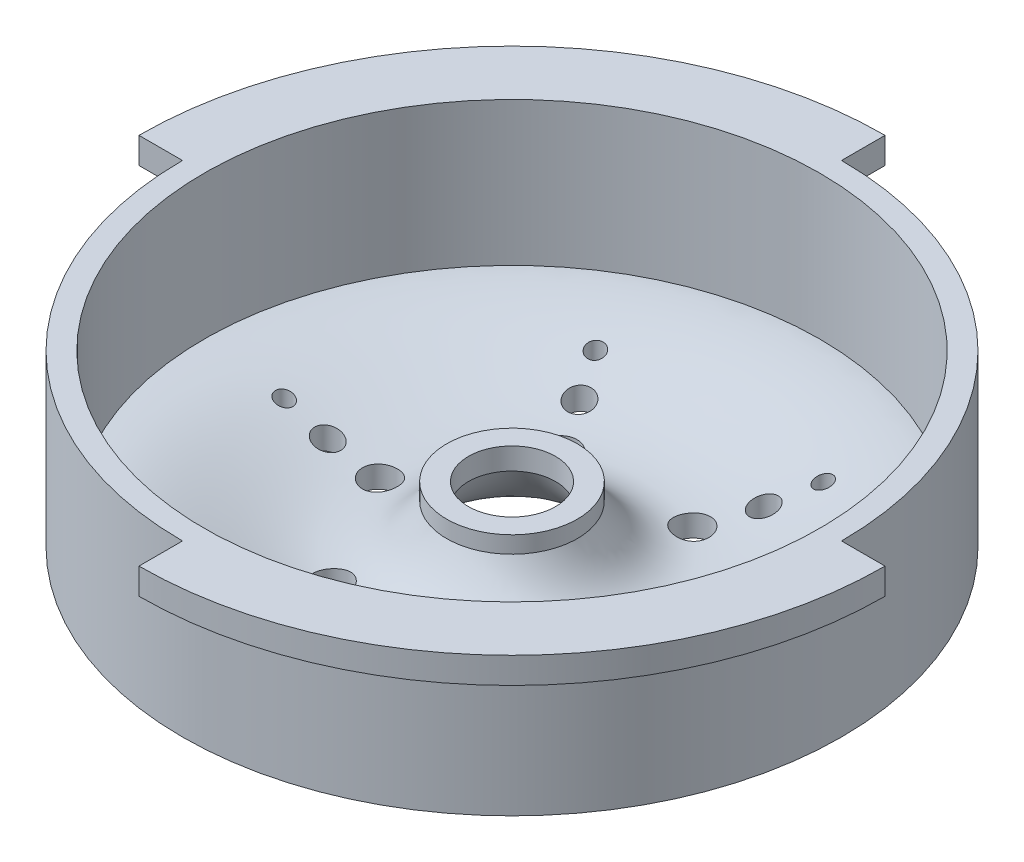
SolidWorks part; units mm, degrees
ref_plane "Front Plane" through (0, 0, 0) normal (0, 0, 1) x (1, 0, 0)
ref_plane "Top Plane" through (0, 0, 0) normal (0, 1, 0) x (1, 0, 0)
ref_plane "Right Plane" through (0, 0, 0) normal (1, 0, 0) x (0, 0, -1)
sketch "Sketch1" plane through (0, 0, 0) normal (0, 0, 1) x (1, 0, 0)
  line L0 (0, 0) -> (0, 16.7848) construction
  line L1 (-12.7, 9.2472) -> (-12.7, 15.5972)
  line L4 (-96.0794, 48.6172) -> (-89.7294, 48.6172)
  line L5 (-19.05, 10.682) -> (-19.05, 15.5972)
  line L8 (-89.7294, 42.2672) -> (-89.7294, 42.2672)
  line L9 (-19.05, 15.5972) -> (-12.7, 15.5972)
  line L11 (-89.7294, 6.7072) -> (-89.7294, 7.8948) construction
  line L12 (-89.7294, 7.8948) -> (-89.7294, 42.2672) construction
  line L14 (-96.0794, 48.6172) -> (-96.0794, -0.9128)
  line L15 (-96.0794, -0.9128) -> (-96.0794, 7.8948) construction
  line L16 (-96.0794, 7.8948) -> (-96.0794, 48.6172) construction
  line L17 (-89.7294, 40.9972) -> (-89.7294, 6.7072)
  line L21 (-89.7294, 48.6172) -> (-89.7294, 40.9972)
  spline S0 degree 3 poles (-12.7, 9.2472) (-24.4163, -16.2586) (-56.9301, -6.4723) (-84.3515, 2.4678) (-96.0794, -0.9128) knots 0 0 0 0 0.639698 1 1 1 1
  spline S1 degree 1 poles (-19.05, 10.682) (-89.7294, 6.7072) knots 0 0 1 1 construction
  spline S2 degree 3 poles (-19.05, 10.682) (-19.2795, 10.2182) (-19.7645, 9.2814) (-20.728, 7.5835) (-21.9651, 5.683) (-23.4727, 3.7603) (-25.5074, 1.6181) (-28.0827, -0.3579) (-31.3013, -1.8994) (-34.8031, -2.7915) (-39.9731, -3.2012) (-47.3576, -2.3166) (-57.1232, 0.3557) (-65.4431, 3.1095) (-72.3975, 5.0904) (-77.8552, 6.2709) (-82.6571, 6.8265) (-86.6412, 6.9026) (-88.7089, 6.7971) (-89.7294, 6.7072) knots 0.011824 0.011824 0.011824 0.011824 0.026126 0.040428 0.069033 0.097637 0.126241 0.183449 0.240657 0.297866 0.355074 0.469491 0.583907 0.698324 0.755532 0.81274 0.869949 0.898553 0.927157 0.927157 0.927157 0.927157
  dimension "D1" = 6.35
  dimension "D2" = 12.7
  dimension "D3" = 6.35
  dimension "D5" = 10.16
  dimension "D7" = 25.4
  dimension "D8" = 25.8304
  dimension "D9" = 32.149
  dimension "D4" = 6.35
revolve "Revolve1" add sketch "Sketch1" angle 360 about L0
sketch "Sketch3" plane through (0, 15.5972, 0) normal (0, 1, 0) x (1, 0, 0)
  circle A0 centre (38.49, 0) radius 5.08
  circle A1 centre (53.73, 0) radius 3.81
  circle A2 centre (66.43, 0) radius 2.54
  circle A3 centre (0, 0) radius 12.7 construction
  circle A4 centre (19.245, -33.3333) radius 5.08
  circle A5 centre (26.865, -46.5316) radius 3.81
  circle A6 centre (33.215, -57.5301) radius 2.54
  circle A7 centre (-19.245, -33.3333) radius 5.08
  circle A8 centre (-26.865, -46.5316) radius 3.81
  circle A9 centre (-33.215, -57.5301) radius 2.54
  circle A10 centre (-38.49, 0) radius 5.08
  circle A11 centre (-53.73, 0) radius 3.81
  circle A12 centre (-66.43, 0) radius 2.54
  circle A13 centre (-19.245, 33.3333) radius 5.08
  circle A14 centre (-26.865, 46.5316) radius 3.81
  circle A15 centre (-33.215, 57.5301) radius 2.54
  circle A16 centre (19.245, 33.3333) radius 5.08
  circle A17 centre (26.865, 46.5316) radius 3.81
  circle A18 centre (33.215, 57.5301) radius 2.54
  point P41 (0, 0)
  dimension "D1" = 10.16
  dimension "D2" = 7.62
  dimension "D3" = 5.08
  dimension "D5" = 38.49
  dimension "D6" = 12.7
  dimension "D4" = 15.24
  dimension "D7" = 6
extrude "Cut-Extrude2" cut sketch "Sketch3" against normal through all
sketch "Sketch6" plane through (0, 48.6172, 0) normal (0, 1, 0) x (1, 0, 0)
  line L0 (0, 0) -> (-108.7794, 0) construction
  line L1 (-108.7794, 0) -> (-95.1008, -13.6787) construction
  line L2 (0, -108.7794) -> (0, 108.7794) construction
  line L3 (0, 108.7794) -> (0, 0) construction
  line L4 (0, 0) -> (108.7794, 0) construction
  line L5 (0, 96.0794) -> (0, 108.7794)
  line L6 (96.0794, 0) -> (108.7794, 0)
  line L7 (-108.7794, 0) -> (-96.0794, 0)
  line L8 (0, -96.0794) -> (0, -108.7794)
  arc A0 (0, -108.7794) -> (108.7794, 0) centre (0, 0) ccw
  arc A1 (0, -96.0794) -> (96.0794, 0) centre (0, 0) ccw
  arc A2 (0, 108.7794) -> (-108.7794, 0) centre (0, 0) ccw
  arc A3 (0, 96.0794) -> (-96.0794, 0) centre (0, 0) ccw
  dimension "D1" = 12.7
extrude "Boss-Extrude1" add sketch "Sketch6" against normal blind 7.62
